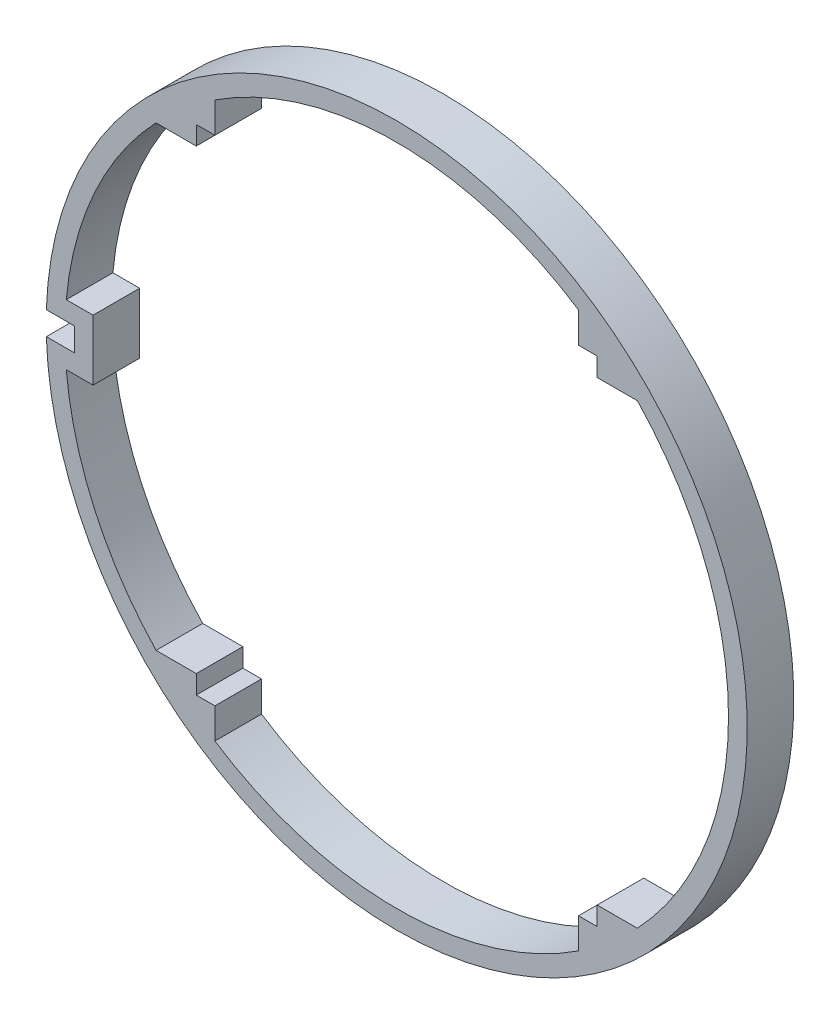
SolidWorks part; units mm, degrees
ref_plane "Front Plane" through (0, 0, 0) normal (1, 0, 0) x (0, 1, 0)
ref_plane "Top Plane" through (0, 0, 0) normal (0, 0, 1) x (0, 1, 0)
ref_plane "Right Plane" through (0, 0, 0) normal (0, 1, 0) x (-1, 0, 0)
sketch "Sketch1" plane through (0, 0, 0) normal (0, 0, 1) x (0, 1, 0)
  line L2 (-2.5003, 75.1584) -> (-2.5003, 71.1392)
  line L4 (2.5003, 75.1584) -> (2.5003, 71.1392)
  line L6 (-2.5003, 71.1392) -> (-2.5003, 69.1392)
  line L7 (-2.5003, 69.1392) -> (2.5003, 69.1392)
  line L8 (2.5003, 69.1392) -> (2.5003, 71.1392)
  line L9 (53, 0) -> (53, -43)
  line L10 (-6.5011, 70.8856) -> (-6.5011, 65.1382)
  line L11 (53, -43) -> (-53, -43)
  line L12 (6.503, 70.8855) -> (6.503, 65.1382)
  line L13 (6.503, 65.1382) -> (-6.5011, 65.1382)
  line L14 (-53, -43) -> (-53, 43)
  line L15 (-53, 43) -> (53, 43)
  line L16 (53, 43) -> (53, 0)
  arc A0 (-2.5003, 75.1584) -> (2.5003, 75.1584) centre (0, 0) ccw
  arc A1 (-6.5011, 70.8856) -> (6.503, 70.8855) centre (0, 0) ccw
extrude "Boss-Extrude1" add sketch "Sketch1" along normal blind 10 contours L12 L13 L10 A1 | L2 L6 L7 L8 L4 A0
sketch "Sketch3" plane through (0, 0, 10) normal (0, 0, 1) x (1, 0, 0)
  line L0 (-0.0001, 52.9854) -> (42.9999, 52.9854)
  line L1 (42.9999, 52.9854) -> (42.9999, -53.0146)
  line L2 (42.9999, -53.0146) -> (-43.0001, -53.0146)
  line L3 (-43.0001, -53.0146) -> (-43.0001, 52.9854)
  line L4 (-43.0001, 52.9854) -> (-0.0001, 52.9854)
  line L5 (-65.1382, 0.0009) -> (71.1831, -0.0009)
  line L6 (-65.1382, 6.503) -> (-65.1382, -6.5011) construction
  line L7 (0, 71.1831) -> (0, -71.1831)
  line L8 (-43.0001, 52.9854) -> (-43.0001, -0.4289)
  line L9 (42.9999, -53.0146) -> (42.9999, -49.0146)
  line L10 (42.9999, -49.0146) -> (55.7299, -49.0146)
  line L11 (42.9999, -53.0146) -> (38.9999, -53.0146)
  line L12 (38.9999, -53.0146) -> (38.9999, -62.7749)
  line L13 (38.9999, -62.7749) -> (55.7299, -49.0146)
  line L14 (42.9999, 52.9854) -> (42.9999, 48.9854)
  line L15 (42.9999, 48.9854) -> (54.9486, 48.9854)
  line L16 (54.9486, 48.9854) -> (38.9999, 61.8044)
  line L17 (38.9999, 61.8044) -> (38.9999, 52.9854)
  line L18 (38.9999, 52.9854) -> (42.9999, 52.9854)
  line L19 (-43.0001, 52.9854) -> (-39.0001, 52.9854)
  line L20 (-39.0001, 52.9854) -> (-39.0001, 61.8044)
  line L21 (-39.0001, 61.8044) -> (-54.5856, 48.9854)
  line L22 (-54.5856, 48.9854) -> (-43.0001, 48.9854)
  line L23 (-43.0001, 48.9854) -> (-43.0001, 52.9854)
  line L24 (-43.0001, -53.0146) -> (-39.0001, -53.0146)
  line L25 (-39.0001, -53.0146) -> (-39.0001, -62.7749)
  line L26 (-39.0001, -62.7749) -> (-54.5856, -49.0146)
  line L27 (-54.5856, -49.0146) -> (-43.0001, -49.0146)
  line L28 (-43.0001, -49.0146) -> (-43.0001, -53.0146)
  arc A0 (-70.8856, -6.5011) -> (-70.8855, 6.503) centre (0, 0) ccw construction
extrude "Boss-Extrude2" add sketch "Sketch3" against normal blind 10 contours L24 L25 L26 L27 L28 | L19 L20 L21 L22 L23 | L14 L15 L16 L17 L18 | L11 L12 L13 L10 L9
